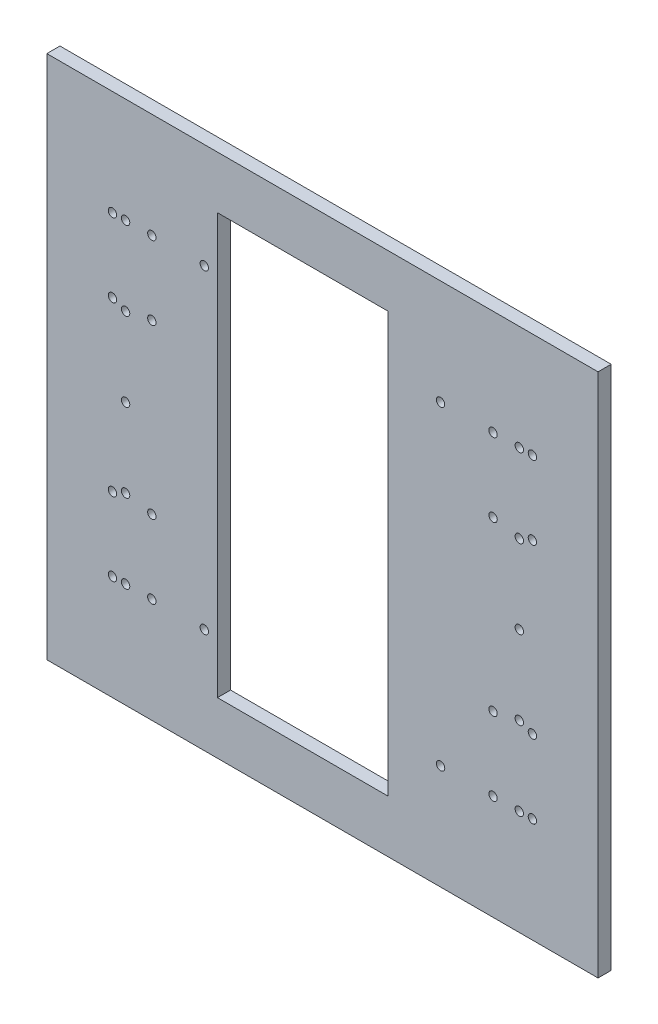
SolidWorks part; units mm, degrees
ref_plane "前视基准面" through (0, 0, 0) normal (0, 0, 1) x (1, 0, 0)
ref_plane "上视基准面" through (0, 0, 0) normal (0, 1, 0) x (1, 0, 0)
ref_plane "右视基准面" through (0, 0, 0) normal (1, 0, 0) x (0, 0, -1)
other "Configuration Table"
sketch "草图2" plane through (0, 0, 0) normal (0, 0, 1) x (1, 0, 0)
  line L0 (-39.2856, 80.1021) -> (-39.2856, -79.8979)
  line L1 (25.7144, 80.1021) -> (-39.2856, 80.1021)
  line L2 (25.7144, -79.8979) -> (25.7144, 80.1021)
  line L3 (-39.2856, -79.8979) -> (25.7144, -79.8979)
  line L4 (105.7144, 100.1021) -> (-104.2856, 100.1021)
  line L5 (-104.2856, 100.1021) -> (-104.2856, -99.8979)
  line L6 (-104.2856, -99.8979) -> (105.7144, -99.8979)
  line L7 (105.7144, -99.8979) -> (105.7144, 100.1021)
  circle A1 centre (-74.2856, -59.8979) radius 1.6
  circle A2 centre (75.7144, 60.1021) radius 1.6
  circle A3 centre (-74.2856, 30.1021) radius 1.6
  circle A4 centre (-74.2856, 0.1021) radius 1.6
  circle A5 centre (-74.2856, -29.8979) radius 1.6
  circle A6 centre (-44.2856, -59.8979) radius 1.6
  circle A7 centre (-44.2856, 60.1021) radius 1.6
  circle A15 centre (45.7144, 60.1021) radius 1.6
  circle A16 centre (75.7144, -29.8979) radius 1.6
  circle A17 centre (75.7144, 0.1021) radius 1.6
  circle A18 centre (45.7144, -59.8979) radius 1.6
  circle A19 centre (75.7144, 30.1021) radius 1.6
  circle A20 centre (75.7144, -59.8979) radius 1.6
  circle A21 centre (-74.2856, 60.1021) radius 1.6
  dimension "D1" = 210
extrude "凸台-拉伸1" add sketch "草图2" along normal blind 5
sketch "草图5" plane through (0, 0, 5) normal (0, 0, 1) x (1, 0, 0)
  line L0 (-104.2856, 0.1021) -> (105.7144, 0.1021)
  line L1 (-79.2856, 60.1021) -> (-64.2856, 60.1021)
  line L2 (-79.2856, 60.1021) -> (-79.2856, 32.1021)
  line L3 (-79.2856, 32.1021) -> (-64.2856, 32.1021)
  line L4 (105.7144, -99.8979) -> (105.7144, 100.1021)
  line L5 (105.7144, 100.1021) -> (-104.2856, 100.1021)
  line L6 (-104.2856, 100.1021) -> (-104.2856, -99.8979)
  line L7 (-104.2856, -99.8979) -> (105.7144, -99.8979)
  line L8 (105.7144, -99.8979) -> (105.7144, 100.1021)
  line L9 (105.7144, 100.1021) -> (-104.2856, 100.1021)
  line L10 (-104.2856, 100.1021) -> (-104.2856, -99.8979)
  line L11 (-104.2856, -99.8979) -> (105.7144, -99.8979)
  line L12 (-64.2856, 60.1021) -> (-64.2856, 32.1021)
  line L13 (-79.2856, 60.1021) -> (-64.2856, 32.1021) construction
  line L14 (-79.2856, 32.1021) -> (-64.2856, 60.1021) construction
  line L15 (0.7144, 100.1021) -> (0.7144, -99.8979)
  line L16 (-79.2856, -31.8979) -> (-64.2856, -31.8979)
  line L17 (-64.2856, -59.8979) -> (-64.2856, -31.8979)
  line L18 (-79.2856, -59.8979) -> (-64.2856, -59.8979)
  line L19 (-79.2856, -59.8979) -> (-79.2856, -31.8979)
  circle A0 centre (-79.2856, 60.1021) radius 1.6
  circle A1 centre (-64.2856, 60.1021) radius 1.6
  circle A2 centre (-64.2856, 32.1021) radius 1.6
  circle A3 centre (-79.2856, 32.1021) radius 1.6
  circle A4 centre (-79.2856, -31.8979) radius 1.6
  circle A5 centre (-64.2856, -31.8979) radius 1.6
  circle A6 centre (-64.2856, -59.8979) radius 1.6
  circle A7 centre (-79.2856, -59.8979) radius 1.6
  circle A8 centre (65.7144, -59.8979) radius 1.6
  circle A9 centre (80.7144, -59.8979) radius 1.6
  circle A10 centre (65.7144, -31.8979) radius 1.6
  circle A11 centre (80.7144, -31.8979) radius 1.6
  circle A12 centre (65.7144, 32.1021) radius 1.6
  circle A13 centre (80.7144, 32.1021) radius 1.6
  circle A14 centre (65.7144, 60.1021) radius 1.6
  circle A15 centre (80.7144, 60.1021) radius 1.6
  point P2 (-71.7856, 46.1021)
  dimension "D6" = 3.2
  dimension "D7" = 3.2
  dimension "D8" = 3.2
  dimension "D9" = 3.2
  dimension "D10" = 3.2
  dimension "D11" = 3.2
  dimension "D12" = 3.2
  dimension "D13" = 3.2
  dimension "D2" = 15
  dimension "D3" = 28
  dimension "D4" = 40
  dimension "D5" = 25
  dimension "D1" = 0
extrude "切除-拉伸1" cut sketch "草图5" against normal through all contours L1 A0 L2 | L2 A0 L1 | L12 A1 L1 | L1 A1 L12 | L3 A3 L2 | L2 A3 L3 | L12 A2 L3 | L3 A2 L12 | L16 A4 L19 | L19 A4 L16 | L17 A5 L16 | L16 A5 L17 | L19 A7 L18 | L18 A7 L19 | L18 A6 L17 | L17 A6 L18 | A8 | A9 | A10 | A11 | A13 | A12 | A14 | A15
